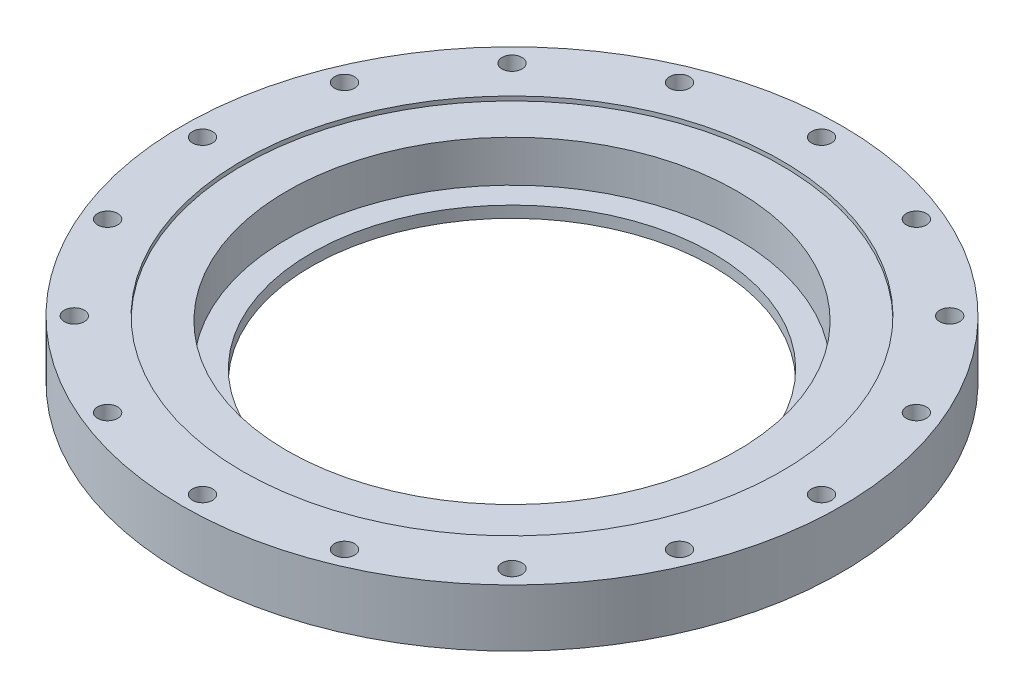
SolidWorks part; units mm, degrees
ref_plane "Front Plane" through (0, 0, 0) normal (0, 0, 1) x (1, 0, 0)
ref_plane "Top Plane" through (0, 0, 0) normal (0, 1, 0) x (1, 0, 0)
ref_plane "Right Plane" through (0, 0, 0) normal (1, 0, 0) x (0, 0, -1)
sketch "Sketch1" plane through (0, 0, 0) normal (0, 1, 0) x (1, 0, 0)
  circle A0 centre (0, 0) radius 57.5
  circle A1 centre (0, 0) radius 39.25
  dimension "D1" = 115
  dimension "D2" = 78.5
extrude "Boss-Extrude1" add sketch "Sketch1" along normal blind 10
sketch "Sketch2" plane through (0, 10, 0) normal (0, 1, 0) x (1, 0, 0)
  circle A0 centre (0, 0) radius 54 construction
  circle A1 centre (0, 54) radius 1.75
  circle A2 centre (20.6649, 49.8895) radius 1.75
  circle A3 centre (38.1838, 38.1838) radius 1.75
  circle A4 centre (49.8895, 20.6649) radius 1.75
  circle A5 centre (54, 0) radius 1.75
  circle A6 centre (49.8895, -20.6649) radius 1.75
  circle A7 centre (38.1838, -38.1838) radius 1.75
  circle A8 centre (20.6649, -49.8895) radius 1.75
  circle A9 centre (0, -54) radius 1.75
  circle A10 centre (-20.6649, -49.8895) radius 1.75
  circle A11 centre (-38.1838, -38.1838) radius 1.75
  circle A12 centre (-49.8895, -20.6649) radius 1.75
  circle A13 centre (-54, 0) radius 1.75
  circle A14 centre (-49.8895, 20.6649) radius 1.75
  circle A15 centre (-38.1838, 38.1838) radius 1.75
  circle A16 centre (-20.6649, 49.8895) radius 1.75
  point P37 (0, 0)
  dimension "D1" = 108
  dimension "D2" = 3.5
  dimension "D3" = 16
extrude "Cut-Extrude1" cut sketch "Sketch2" against normal blind 17
sketch "Sketch3" plane through (0, 10, 0) normal (0, 1, 0) x (1, 0, 0)
  circle A0 centre (0, 0) radius 45 construction
  circle A32 centre (0, 0) radius 47
  point P67 (0, 0)
  dimension "D1" = 90
  dimension "D2" = 2
extrude "Cut-Extrude2" cut sketch "Sketch3" against normal blind 0.75
sketch "Sketch4" plane through (0, 0, 0) normal (0, -1, 0) x (1, 0, 0)
  circle A0 centre (0, 0) radius 50
  dimension "D1" = 100
sketch "Sketch5" plane through (0, 0, 0) normal (0, -1, 0) x (1, 0, 0)
  line L0 (0, 45) -> (0, 0) construction
  line L4 (0, 0) -> (26.5522, 0) construction
  circle A0 centre (0, 45) radius 2
  circle A1 centre (0, 0) radius 45 construction
  circle A2 centre (38.9711, -22.5) radius 2
  circle A3 centre (-38.9711, -22.5) radius 2
  point P11 (0, 0)
  dimension "D1" = 90
  dimension "D2" = 4
  dimension "D4" = 90
  dimension "D3" = 3
extrude "Cut-Extrude3" cut sketch "Sketch5" against normal blind 5
sketch "Sketch6" plane through (0, 0, 0) normal (0, -1, 0) x (1, 0, 0)
  circle A0 centre (0, 0) radius 39.25
  circle A1 centre (0, 0) radius 35
  dimension "D1" = 70
extrude "Boss-Extrude2" add sketch "Sketch6" against normal blind 2
